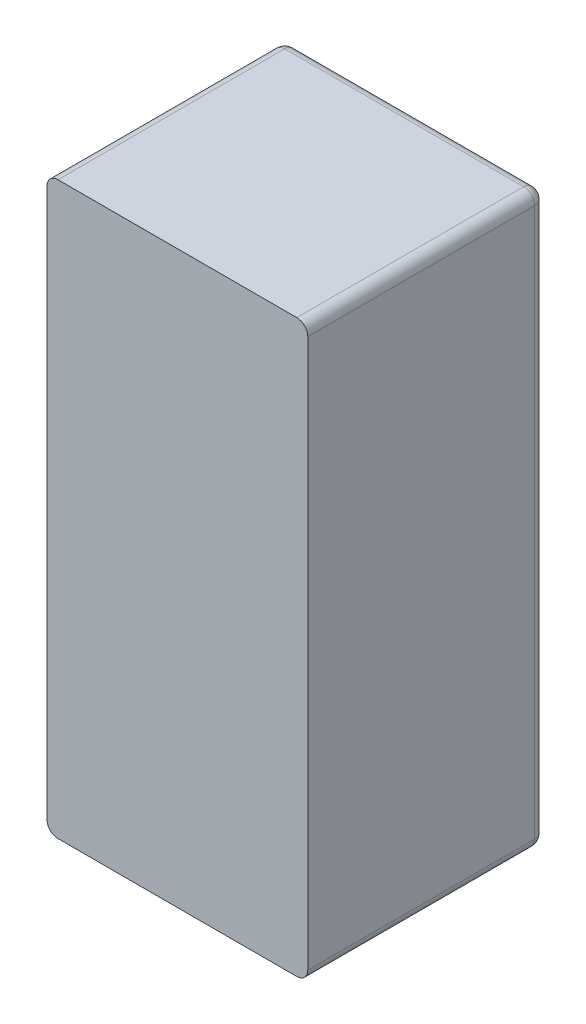
SolidWorks part; units mm, degrees
ref_plane "Front Plane" through (0, 0, 0) normal (0, 0, 1) x (1, 0, 0)
ref_plane "Top Plane" through (0, 0, 0) normal (0, 1, 0) x (1, 0, 0)
ref_plane "Right Plane" through (0, 0, 0) normal (1, 0, 0) x (0, 0, -1)
sketch "Sketch1" plane through (0, 0, 0) normal (0, 1, 0) x (1, 0, 0)
  line L1 (0, 0) -> (-237.998, 0)
  line L2 (0, 0) -> (0, -216.916)
  line L3 (0, -216.916) -> (-237.998, -216.916)
  line L4 (-237.998, 0) -> (-237.998, -216.916)
  dimension "D1" = 216.916
  dimension "D2" = 237.998
extrude "Boss-Extrude1" add sketch "Sketch1" along normal blind 520.7
fillet "Fillet1" radius 10 8 edges at (0, 260.35, 0) (-118.999, 520.7, 0) (-237.998, 260.35, 0) (-118.999, 0, 0) (-237.998, 520.7, 108.458) (-237.998, 0, 108.458) (0, 520.7, 108.458) (0, 0, 108.458)
move or copy body "Body-Move/Copy1" bodies to move or copy 101 copy no translate (118.999, -260.35, -108.458)
